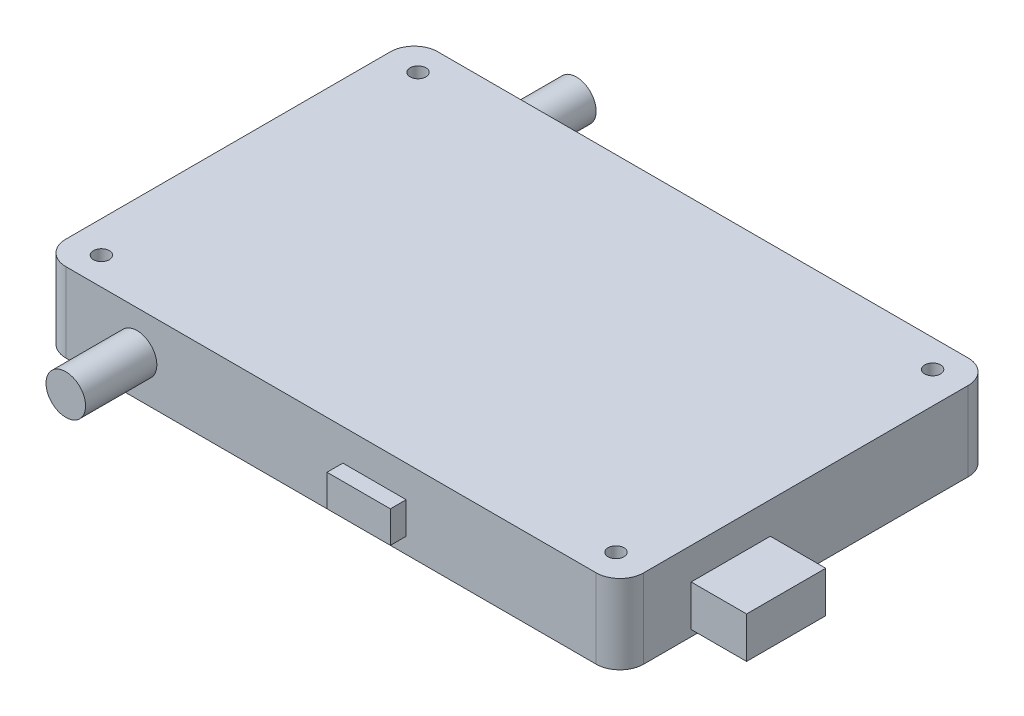
SolidWorks part; units mm, degrees
ref_plane "前视基准面" through (0, 0, 0) normal (0, 0, 1) x (1, 0, 0)
ref_plane "上视基准面" through (0, 0, 0) normal (0, 1, 0) x (1, 0, 0)
ref_plane "右视基准面" through (0, 0, 0) normal (1, 0, 0) x (0, 0, -1)
sketch "草图1" plane through (0, 0, 0) normal (0, 1, 0) x (1, 0, 0)
  line L0 (0, 0) -> (73, 0)
  line L1 (73, 0) -> (73, 47)
  line L2 (73, 47) -> (0, 47)
  line L3 (0, 47) -> (0, 0)
  line L4 (36.5, 0) -> (36.5, 50000) construction
  line L5 (-4.477, 23.5) -> (49995.523, 23.5) construction
  circle A0 centre (4, 3.5) radius 1
  circle A1 centre (4, 43.5) radius 1
  circle A2 centre (69, 3.5) radius 1
  circle A3 centre (69, 43.5) radius 1
  point P7 (36.5, 0)
  point P10 (36.5, 23.5)
  point P15 (0, 23.5)
  point P16 (0, 23.5)
  point P17 (0, 23.5)
  dimension "D3" = 32.5
  dimension "D5" = 2
  dimension "D1" = 73
  dimension "D2" = 47
  dimension "D4" = 20
extrude "凸台-拉伸1" add sketch "草图1" along normal blind 10
fillet "圆角1" radius 3 4 edges at (73, 5, -47) (73, 5, 0) (0, 5, -47) (0, 5, 0)
sketch "草图3" plane through (0, 0, 0) normal (0, -1, 0) x (1, 0, 0)
  circle A0 centre (4, -43.5) radius 2
  circle A1 centre (4, -3.5) radius 2
  circle A2 centre (69, -3.5) radius 2
  circle A3 centre (69, -43.5) radius 2
extrude "切除-拉伸1" cut sketch "草图3" against normal blind 1
sketch "草图2" plane through (0, 0, -47) normal (0, 0, -1) x (-1, 0, 0)
  line L0 (0, 10) -> (0, 0) construction
  line L1 (-70, 0) -> (-3, 0) construction
  circle A0 centre (-12, 5) radius 2.5
  dimension "D1" = 12
  dimension "D3" = 5
  dimension "D2" = 5
extrude "凸台-拉伸2" add sketch "草图2" along normal blind 8.5 contours A0
sketch "草图5" plane through (0, 0, 0) normal (0, 0, 1) x (1, 0, 0)
  circle A0 centre (12, 5) radius 2.5
extrude "凸台-拉伸3" add sketch "草图5" along normal blind 9
sketch "草图6" plane through (0, 0, 0) normal (0, 0, 1) x (1, 0, 0)
  line L0 (38, 2) -> (38, 6)
  line L1 (38, 6) -> (46, 6)
  line L2 (46, 6) -> (46, 2)
  line L3 (46, 2) -> (38, 2)
  line L4 (0, 0) -> (0, 10) construction
  line L6 (3, 10) -> (70, 10) construction
  dimension "D1" = 38
  dimension "D2" = 8
  dimension "D3" = 4
  dimension "D4" = 4
extrude "LAN口预留" add sketch "草图6" along normal blind 2
sketch "草图7" plane through (0, 0, -47) normal (0, 0, -1) x (-1, 0, 0)
  line L0 (-48, 6) -> (-48, 2)
  line L1 (-48, 2) -> (-59, 2)
  line L2 (-59, 2) -> (-59, 6)
  line L3 (-59, 6) -> (-48, 6)
  line L4 (0, 10) -> (0, 0) construction
  line L6 (-70, 10) -> (-3, 10) construction
  dimension "D1" = 48
  dimension "D2" = 11
  dimension "D3" = 4
  dimension "D4" = 4
extrude "COM口预留" add sketch "草图7" along normal blind 2
sketch "草图8" plane through (73, 0, 0) normal (1, 0, 0) x (0, 0, -1)
  line L0 (19, 0.8) -> (9, 0.8)
  line L1 (9, 0.8) -> (9, 6)
  line L4 (19, 0.8) -> (19, 6)
  line L5 (19, 6) -> (9, 6)
  line L6 (0, 0) -> (0, 10) construction
  line L7 (3, 10) -> (44, 10) construction
  dimension "D1" = 10
  dimension "D2" = 9
  dimension "D3" = 5.2
  dimension "D4" = 4
extrude "XT30预留" add sketch "草图8" along normal blind 7
